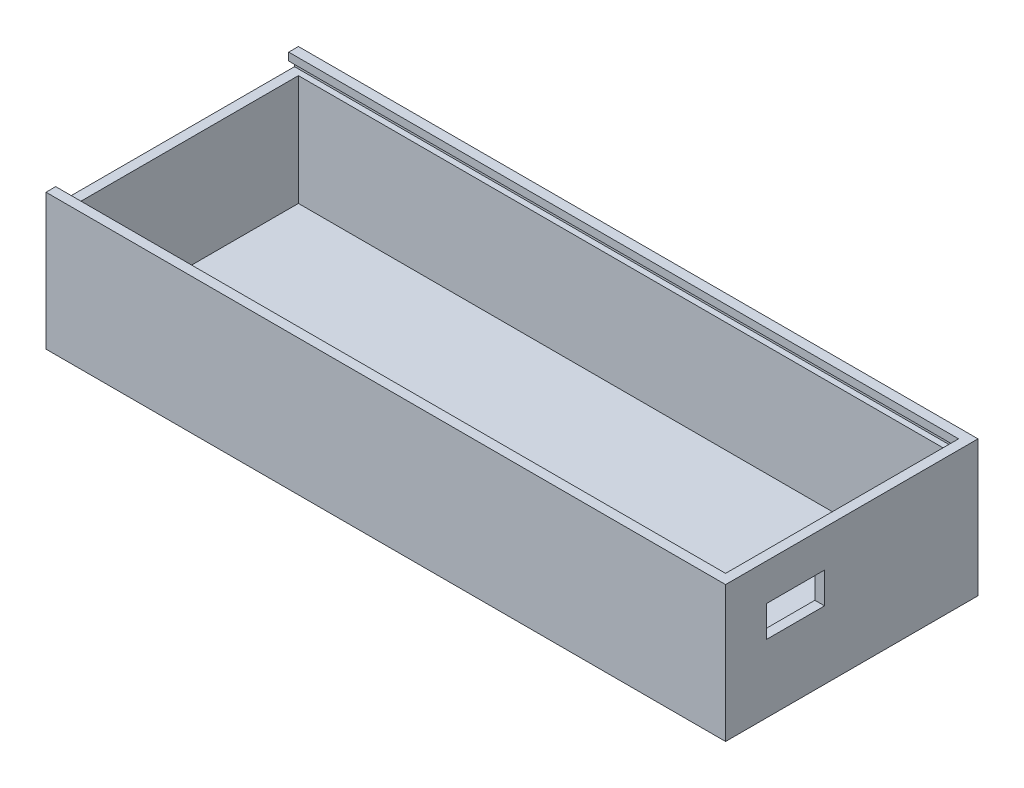
SolidWorks part; units mm, degrees
ref_plane "Front Plane" through (0, 0, 0) normal (0, 0, 1) x (1, 0, 0)
ref_plane "Top Plane" through (0, 0, 0) normal (0, 1, 0) x (1, 0, 0)
ref_plane "Right Plane" through (0, 0, 0) normal (1, 0, 0) x (0, 0, -1)
other "Configuration Table"
sketch "Sketch2" plane through (0, 0, 0) normal (0, 1, 0) x (1, 0, 0)
  line L1 (-91.6048, 59.6686) -> (83.3952, 59.6686)
  line L2 (-91.6048, 59.6686) -> (-91.6048, -5.3314)
  line L3 (-91.6048, -5.3314) -> (83.3952, -5.3314)
  line L4 (83.3952, 59.6686) -> (83.3952, -5.3314)
  dimension "D1" = 65
  dimension "D2" = 175
extrude "Boss-Extrude1" add sketch "Sketch2" along normal blind 35
sketch "Sketch3" plane through (0, 35, 0) normal (0, 1, 0) x (1, 0, 0)
  line L1 (-89.1048, 57.1686) -> (80.8952, 57.1686)
  line L2 (-89.1048, 57.1686) -> (-89.1048, -2.8314)
  line L3 (-89.1048, -2.8314) -> (80.8952, -2.8314)
  line L4 (80.8952, 57.1686) -> (80.8952, -2.8314)
  line L6 (-91.6048, 59.6686) -> (-91.6048, -5.3314) construction
  line L7 (83.3952, 59.6686) -> (-91.6048, 59.6686) construction
  dimension "D1" = 170
  dimension "D2" = 60
  dimension "D3" = 2.5
  dimension "D4" = 2.5
extrude "Cut-Extrude1" cut sketch "Sketch3" against normal blind 32.5
sketch "Sketch4" plane through (83.3952, 0, 0) normal (1, 0, 0) x (0, 0, -1)
  line L8 (5.1686, 25.5) -> (20.1686, 25.5)
  line L9 (5.1686, 25.5) -> (5.1686, 17.5)
  line L10 (5.1686, 17.5) -> (20.1686, 17.5)
  line L11 (20.1686, 25.5) -> (20.1686, 17.5)
  dimension "D1" = 15
  dimension "D2" = 8
extrude "Cut-Extrude3" cut sketch "Sketch4" against normal up to surface (172.5 mm away) up to face at (-89.1048, 18.75, -27.1686)
sketch "Sketch5" plane through (-91.6048, 0, 0) normal (-1, 0, 0) x (0, 0, 1)
  line L0 (-59.6686, 35) -> (-59.6686, 0) construction
  line L1 (-58.6686, 33) -> (4.3314, 33)
  line L2 (-58.6686, 33) -> (-58.6686, 31)
  line L3 (-58.6686, 31) -> (4.3314, 31)
  line L4 (4.3314, 33) -> (4.3314, 31)
  line L5 (5.3314, 35) -> (5.3314, 0) construction
  line L6 (-59.6686, 35) -> (5.3314, 35) construction
  dimension "D1" = 1
  dimension "D2" = 1
  dimension "D3" = 2
  dimension "D4" = 2
extrude "Cut-Extrude5" cut sketch "Sketch5" against normal blind 173.5
sketch "Sketch7" plane through (-91.6048, 0, 0) normal (-1, 0, 0) x (0, 0, 1)
  line L0 (-59.6686, 35) -> (5.3314, 35) construction
  line L1 (-57.1686, 35) -> (2.8314, 35)
  line L2 (-57.1686, 35) -> (-57.1686, 33)
  line L3 (-57.1686, 33) -> (2.8314, 33)
  line L4 (2.8314, 35) -> (2.8314, 33)
  line L5 (4.3314, 33) -> (-58.6686, 33) construction
  line L6 (-59.6686, 35) -> (-59.6686, 0) construction
  line L8 (5.3314, 35) -> (5.3314, 0) construction
  dimension "D1" = 2.5
  dimension "D2" = 2.5
extrude "Cut-Extrude6" cut sketch "Sketch7" against normal blind 2.5
